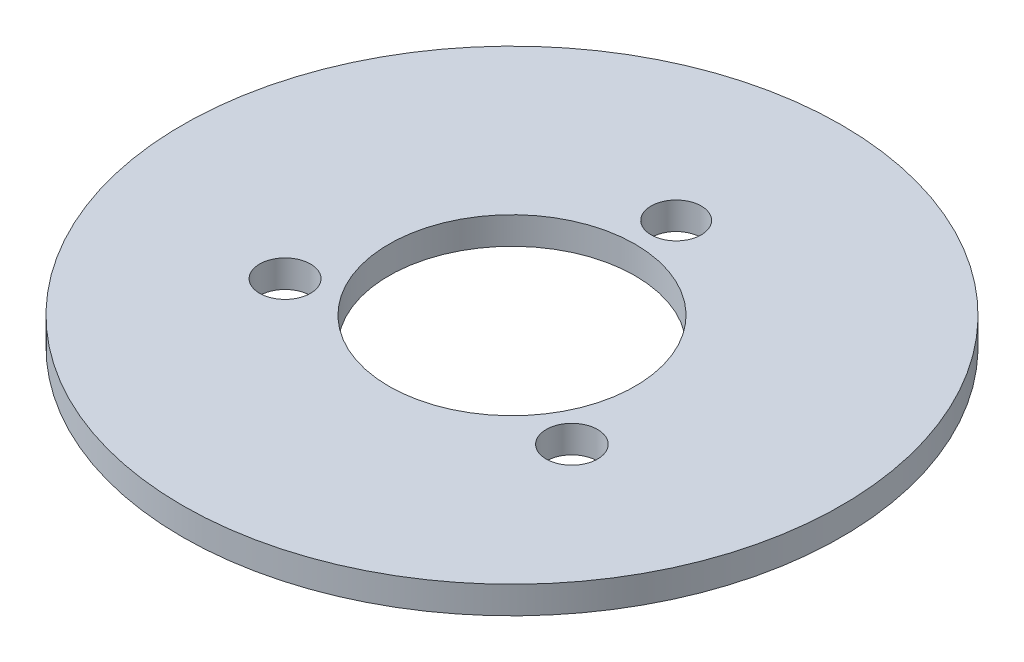
SolidWorks part; units mm, degrees
ref_plane "Front Plane" through (0, 0, 0) normal (0, 0, 1) x (1, 0, 0)
ref_plane "Top Plane" through (0, 0, 0) normal (0, 1, 0) x (1, 0, 0)
ref_plane "Right Plane" through (0, 0, 0) normal (1, 0, 0) x (0, 0, -1)
sketch "Sketch1" plane through (0, 0, 0) normal (0, 1, 0) x (1, 0, 0)
  line L0 (0, 0) -> (0, 19.05) construction
  line L1 (0, 0) -> (11.1378, -6.4304) construction
  line L2 (11.1378, -6.4304) -> (16.4445, -9.4942) construction
  line L3 (0, 0) -> (-11.2031, -6.3158) construction
  line L4 (-11.2031, -6.3158) -> (-16.8412, -9.4942) construction
  circle A0 centre (0, 0) radius 38.2439
  circle A1 centre (0, 0) radius 12.8604
  arc A2 (0.1319, 12.8601) -> (11.1378, -6.4304) centre (0, 0) cw
  arc A3 (0.1319, 12.8601) -> (-11.2031, -6.3158) centre (0, 0) cw
  circle A4 centre (-16.8412, -9.4942) radius 2.9529
  circle A5 centre (16.4445, -9.4942) radius 2.9796
  circle A6 centre (0, 19.05) radius 2.9091
extrude "Boss-Extrude1" add sketch "Sketch1" along normal blind 3.175
sketch "Sketch2" plane through (0, 0, 0) normal (0, -1, 0) x (1, 0, 0)
  circle A0 centre (0, 0) radius 14.2875
extrude "Cut-Extrude1" cut sketch "Sketch2" against normal blind 3.175
